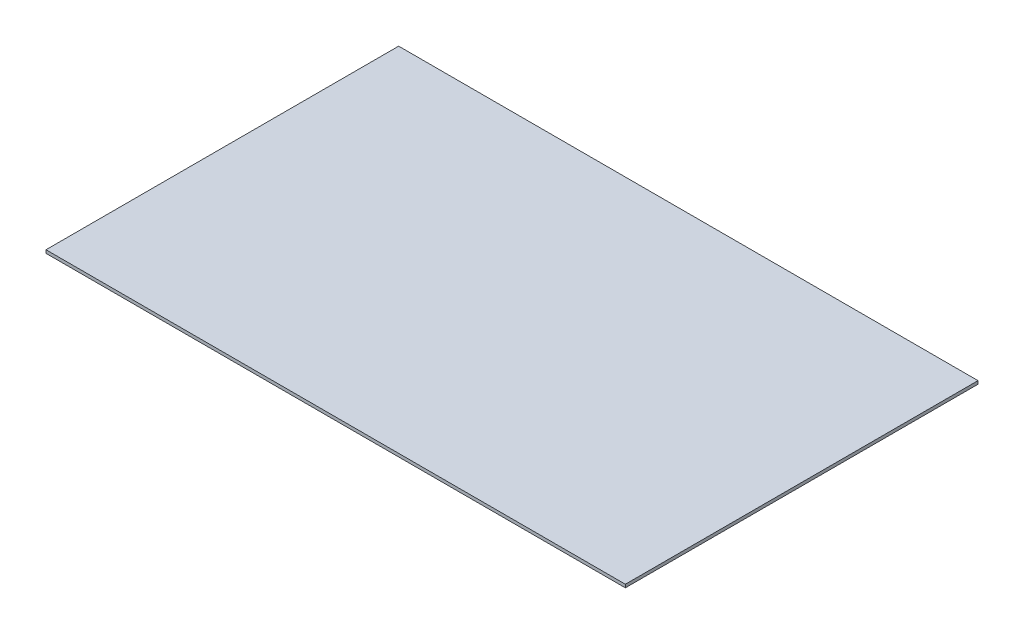
SolidWorks part; units mm, degrees
material "ABS PC"
ref_plane "Front Plane" through (0, 0, 0) normal (0, 0, 1) x (1, 0, 0)
ref_plane "Top Plane" through (0, 0, 0) normal (0, 1, 0) x (1, 0, 0)
ref_plane "Right Plane" through (0, 0, 0) normal (1, 0, 0) x (0, 0, -1)
sketch "Sketch1" plane through (0, 0, 0) normal (0, 1, 0) x (1, 0, 0)
  line L1 (0, 0) -> (584.2, 0)
  line L2 (0, 0) -> (0, 355.6)
  line L3 (0, 355.6) -> (584.2, 355.6)
  line L4 (584.2, 0) -> (584.2, 355.6)
  dimension "D1" = 584.2
  dimension "D2" = 355.6
extrude "Boss-Extrude1" add sketch "Sketch1" along normal blind 3.175
